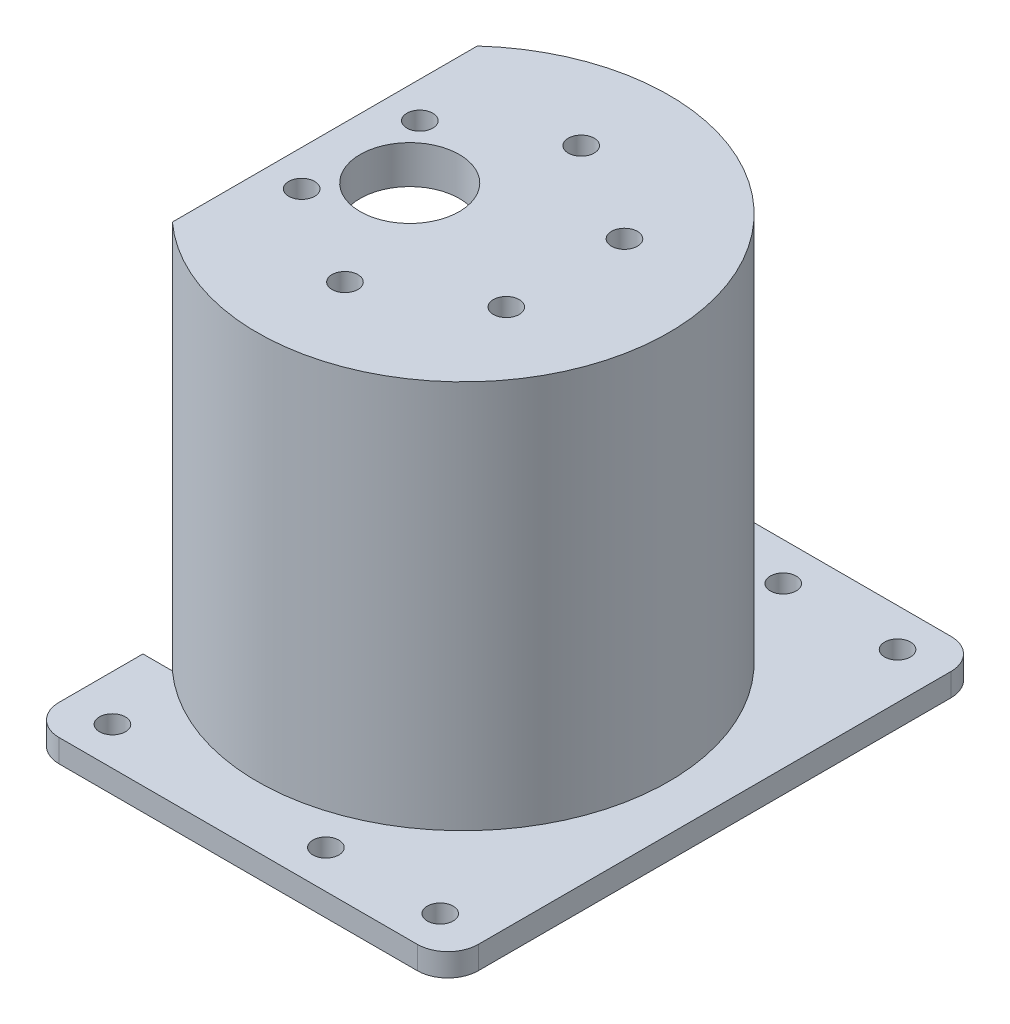
SolidWorks part; units mm, degrees
ref_plane "Płaszczyzna przednia" through (0, 0, 0) normal (0, 0, 1) x (1, 0, 0)
ref_plane "Płaszczyzna górna" through (0, 0, 0) normal (0, 1, 0) x (1, 0, 0)
ref_plane "Płaszczyzna prawa" through (0, 0, 0) normal (1, 0, 0) x (0, 0, -1)
sketch "Szkic1" plane through (0, 0, 0) normal (0, 1, 0) x (1, 0, 0)
  line L0 (-27.5, 20) -> (-12.5, 20)
  line L1 (-23.5, 35) -> (23.5, 35)
  line L2 (-27.5, 31) -> (-27.5, 20)
  line L3 (-23.5, -35) -> (23.5, -35)
  line L4 (27.5, 31) -> (27.5, -31)
  line L5 (-27.5, 35) -> (27.5, -35) construction
  line L6 (-27.5, -35) -> (27.5, 35) construction
  line L7 (-27.5, -20) -> (-12.5, -20)
  line L8 (-27.5, -20) -> (-27.5, -31)
  arc A0 (-27.5, -31) -> (-23.5, -35) centre (-23.5, -31) ccw
  arc A1 (23.5, -35) -> (27.5, -31) centre (23.5, -31) ccw
  arc A2 (23.5, 35) -> (27.5, 31) centre (23.5, 31) cw
  arc A3 (-23.5, 35) -> (-27.5, 31) centre (-23.5, 31) ccw
  arc A4 (-11.38, -20.16) -> (-11.38, 20.16) centre (-5.5, 0) ccw
  arc A5 (-12.5, -20) -> (-11.38, -20.16) centre (-12.5, -24) cw
  arc A6 (-12.5, 20) -> (-11.38, 20.16) centre (-12.5, 24) ccw
  point P0 (0, 0)
  dimension "D1" = 4
  dimension "D2" = 40
  dimension "D3" = 4
  dimension "D5" = 21
  dimension "D4" = 70
  dimension "D6" = 55
  dimension "D7" = 33
extrude "Dodanie-wyciągnięcie1" add sketch "Szkic1" along normal blind 3
sketch "Szkic2" plane through (0, 3, 0) normal (0, 1, 0) x (1, 0, 0)
  line L0 (-12.5, -20) -> (-27.5, -20) construction
  line L1 (-27.5, 20) -> (-12.5, 20) construction
  line L2 (-12.5, -20) -> (-23.6384, -20)
  line L3 (-23.6384, 20) -> (-12.5, 20)
  arc A0 (-11.38, -20.16) -> (-12.5, -20) centre (-12.5, -24) ccw construction
  arc A1 (-12.5, 20) -> (-11.38, 20.16) centre (-12.5, 24) ccw construction
  arc A2 (-11.38, -20.16) -> (-11.38, 20.16) centre (-5.5, 0) ccw construction
  arc A3 (-11.38, -20.16) -> (-12.5, -20) centre (-12.5, -24) ccw
  arc A4 (-12.5, 20) -> (-11.38, 20.16) centre (-12.5, 24) ccw
  arc A5 (-11.38, -20.16) -> (-11.38, 20.16) centre (-5.5, 0) ccw
  arc A6 (-23.6384, -20) -> (-23.6384, 20) centre (-5.5, 0) ccw
  dimension "D1" = 54
extrude "Dodanie-wyciągnięcie2" add sketch "Szkic2" along normal blind 51
sketch "Szkic3" plane through (0, 54, 0) normal (0, 1, 0) x (1, 0, 0)
  line L0 (-23.6384, 20) -> (-23.6384, -20)
  arc A0 (-23.6384, -20) -> (-23.6384, 20) centre (-5.5, 0) ccw construction
  arc A1 (-23.6384, -20) -> (-23.6384, 20) centre (-5.5, 0) ccw
extrude "Dodanie-wyciągnięcie3" add sketch "Szkic3" against normal blind 5
sketch "Szkic4" plane through (0, 3, 0) normal (0, 1, 0) x (1, 0, 0)
  line L0 (-23.5, -35) -> (23.5, -35) construction
  line L1 (-27.5, -20) -> (-27.5, -31) construction
  circle A0 centre (-21.5, -30) radius 1.7
  circle A1 centre (21.5, -30) radius 1.7
  circle A2 centre (21.5, 30) radius 1.7
  circle A3 centre (-21.5, 30) radius 1.7
  circle A4 centre (6.5, -30) radius 1.7
  circle A5 centre (6.5, 30) radius 1.7
  dimension "D1" = 3.4
  dimension "D6" = 15
  dimension "D7" = 43
  dimension "D8" = 60
  dimension "D2" = 5
  dimension "D3" = 6
  dimension "D4" = 2
  dimension "D5" = 2
extrude "Wytnij-wyciągnięcie1" cut sketch "Szkic4" against normal blind 5
sketch "Szkic5" plane through (0, 54, 0) normal (0, 1, 0) x (1, 0, 0)
  line L0 (-5.5, 0) -> (-5.5, -15.5) construction
  circle A0 centre (-12.5, 0) radius 6.5
  arc A1 (-23.6384, -20) -> (-23.6384, 20) centre (-5.5, 0) ccw construction
  circle A2 centre (-5.5, -15.5) radius 1.7
  circle A3 centre (-18.9234, -7.75) radius 1.7
  circle A4 centre (-18.9234, 7.75) radius 1.7
  circle A5 centre (-5.5, 15.5) radius 1.7
  circle A6 centre (7.9234, 7.75) radius 1.7
  circle A7 centre (7.9234, -7.75) radius 1.7
  point P23 (-5.5, 0)
  dimension "D1" = 7
  dimension "D2" = 13
  dimension "D3" = 3.4
  dimension "D4" = 15.5
  dimension "D5" = 6
extrude "Wytnij-wyciągnięcie2" cut sketch "Szkic5" against normal blind 5
